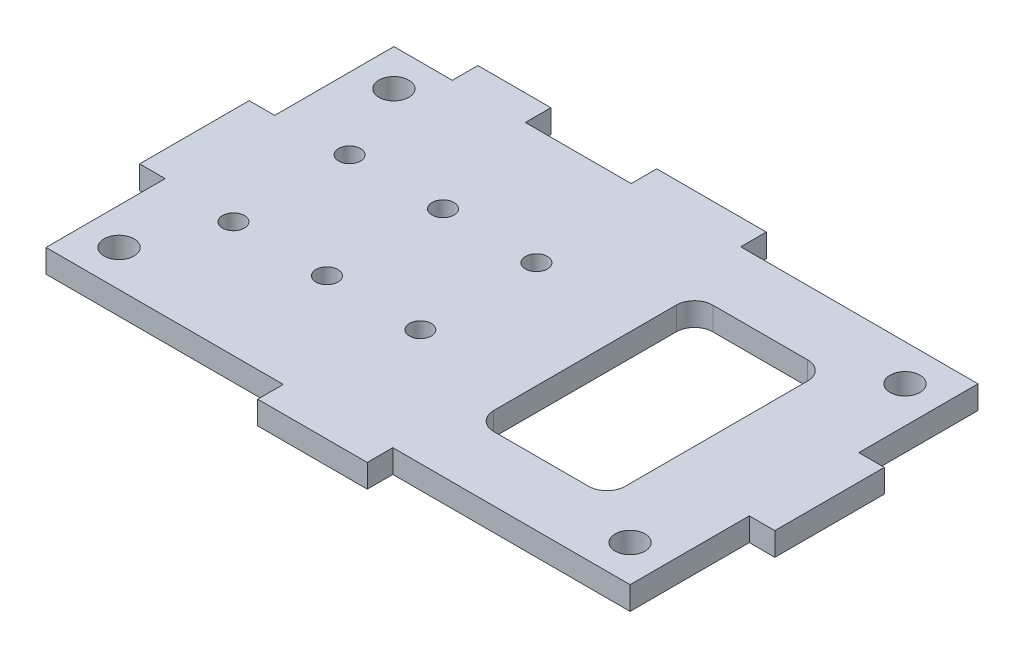
SolidWorks part; units mm, degrees
ref_plane "Front Plane" through (0, 0, 0) normal (0, 0, 1) x (1, 0, 0)
ref_plane "Top Plane" through (0, 0, 0) normal (0, 1, 0) x (1, 0, 0)
ref_plane "Right Plane" through (0, 0, 0) normal (1, 0, 0) x (0, 0, -1)
sketch "Sketch2" plane through (0, 0, 0) normal (0, 1, 0) x (1, 0, 0)
  line L0 (0, -1.7463) -> (0, 1.7463) construction
  line L1 (-40, 23.825) -> (40, 23.825)
  line L2 (-40, 23.825) -> (-40, -23.825)
  line L3 (-40, -23.825) -> (40, -23.825)
  line L4 (40, 23.825) -> (40, -23.825)
  point P4 (0, -23.825)
  dimension "D1" = 47.65
  dimension "D2" = 80
  dimension "D4" = 23.825
extrude "Boss-Extrude1" add sketch "Sketch2" along normal blind 3.175
sketch "Sketch3" plane through (0, 3.175, 0) normal (0, 1, 0) x (1, 0, 0)
  line L0 (40, 23.825) -> (-40, 23.825) construction
  line L1 (-7.5, 23.825) -> (7.5, 23.825)
  line L2 (-7.5, 23.825) -> (-7.5, 27.325)
  line L3 (-7.5, 27.325) -> (7.5, 27.325)
  line L4 (7.5, 23.825) -> (7.5, 27.325)
  point P6 (0, 23.825)
  dimension "D1" = 15
  dimension "D2" = 3.5
  dimension "D3" = 0
extrude "Boss-Extrude2" add sketch "Sketch3" against normal blind 3.175
sketch "Sketch4" plane through (0, 3.175, 0) normal (0, 1, 0) x (1, 0, 0)
  line L0 (-40, 23.825) -> (-40, -23.825) construction
  line L1 (-40, 7.5) -> (-43.5, 7.5)
  line L2 (-40, 7.5) -> (-40, -7.5)
  line L3 (-40, -7.5) -> (-43.5, -7.5)
  line L4 (-43.5, 7.5) -> (-43.5, -7.5)
  dimension "D1" = 15
  dimension "D2" = 3.5
  dimension "D3" = 7.5
extrude "Boss-Extrude3" add sketch "Sketch4" against normal blind 3.175
mirror "Mirror1" about plane through (0, 0, 0) normal (1, 0, 0) of "Boss-Extrude3"
mirror "Mirror2" about plane through (0, 0, 0) normal (0, 0, 1) of "Boss-Extrude2", "Mirror1"
sketch "Sketch5" plane through (0, 3.175, 0) normal (0, 1, 0) x (1, 0, 0)
  line L1 (-40, 23.825) -> (-40, 7.5) construction
  line L2 (-7.5, 23.825) -> (-40, 23.825) construction
  circle A0 centre (-35, 18.825) radius 2.05
  dimension "D2" = 4.1
  dimension "D3" = 5
  dimension "D1" = 5
extrude "Cut-Extrude1" cut sketch "Sketch5" against normal blind 20
sketch "Sketch6" plane through (0, 3.175, 0) normal (0, 1, 0) x (1, 0, 0)
  line L1 (10, 15) -> (28, 15)
  line L2 (10, 15) -> (10, -15)
  line L3 (10, -15) -> (28, -15)
  line L4 (28, 15) -> (28, -15)
  point P4 (28, 0)
  dimension "D1" = 30
  dimension "D2" = 18
  dimension "D3" = 0
  dimension "D4" = 10
extrude "Cut-Extrude2" cut sketch "Sketch6" against normal through all
fillet "Fillet1" radius 2.5 4 edges at (28, 1.5875, 15) (10, 1.5875, 15) (28, 1.5875, -15) (10, 1.5875, -15)
mirror "Mirror3" about plane through (0, 0, 0) normal (1, 0, 0) of "Cut-Extrude1"
mirror "Mirror4" about plane through (0, 0, 0) normal (0, 0, 1) of "Mirror3", "Cut-Extrude1"
sketch "Sketch8" plane through (0, 3.175, 0) normal (0, 1, 0) x (1, 0, 0)
  line L0 (-1.7463, 0) -> (1.7463, 0) construction
  line L1 (-40, 23.825) -> (-40, 7.5) construction
  circle A0 centre (-30.2, 7.95) radius 1.5
  dimension "D1" = 3
  dimension "D2" = 7.95
  dimension "D3" = 9.8
extrude "Cut-Extrude4" cut sketch "Sketch8" against normal blind 10
pattern_linear "LPattern1" count 3 spacing 12.8 along (1, 0, 0) of "Cut-Extrude4"
mirror "Mirror5" about plane through (0, 0, 0) normal (0, 0, 1) of "LPattern1", "Cut-Extrude4"
sketch "Sketch9" plane through (0, 0, 0) normal (0, 1, 0) x (1, 0, 0)
  line L0 (-7.5, 23.825) -> (-40, 23.825) construction
  line L1 (-32, 23.825) -> (-22, 23.825)
  line L2 (-32, 23.825) -> (-32, 27.325)
  line L3 (-32, 27.325) -> (-22, 27.325)
  line L4 (-22, 23.825) -> (-22, 27.325)
  line L5 (-40, 23.825) -> (-40, 7.5) construction
  dimension "D1" = 8
  dimension "D2" = 10
  dimension "D3" = 3.5
extrude "Boss-Extrude4" add sketch "Sketch9" along normal blind 3.175
